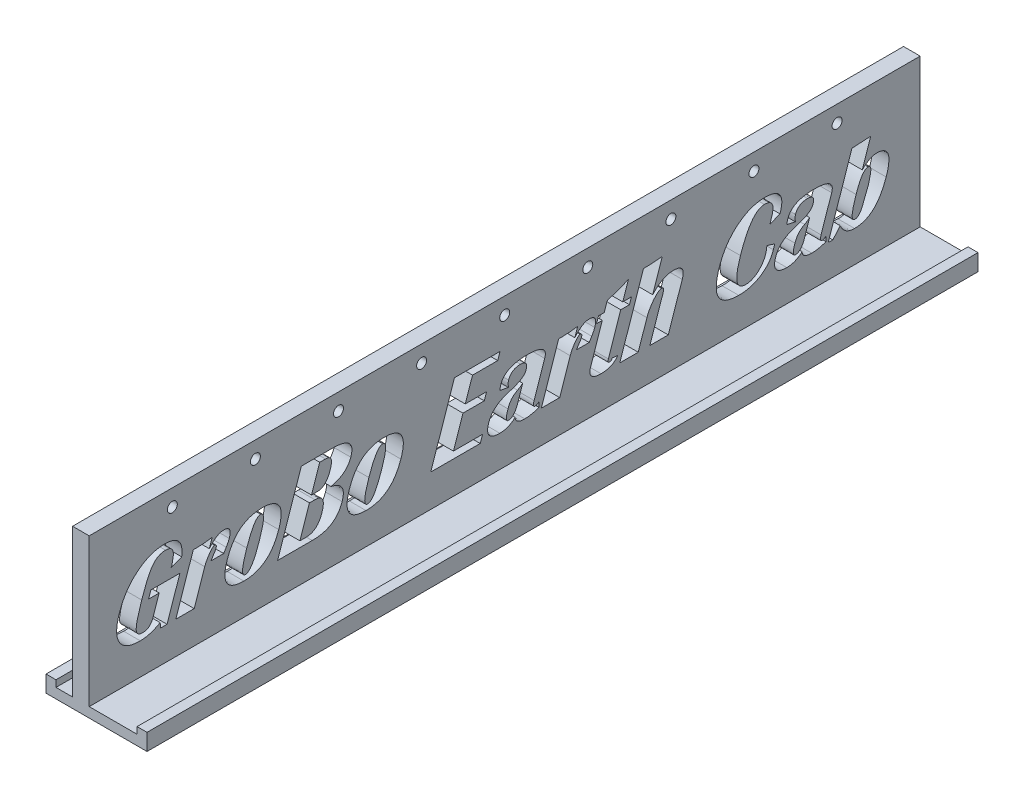
SolidWorks part; units mm, degrees
material "Acrylic (Medium-high impact)"
ref_plane "Front Plane" through (0, 0, 0) normal (0, 0, 1) x (1, 0, 0)
ref_plane "Top Plane" through (0, 0, 0) normal (0, 1, 0) x (1, 0, 0)
ref_plane "Right Plane" through (0, 0, 0) normal (1, 0, 0) x (0, 0, -1)
sketch "Sketch1" plane through (0, 0, 0) normal (0, 0, 1) x (1, 0, 0)
  line L0 (0, 10) -> (0, 0)
  line L1 (0, 0) -> (60.8, 0)
  line L2 (60.8, 0) -> (60.8, 10)
  line L3 (60.8, 10) -> (54.8, 10)
  line L4 (54.8, 10) -> (54.8, 6)
  line L5 (54.8, 6) -> (26, 6)
  line L6 (26, 6) -> (26, 95)
  line L7 (26, 95) -> (16, 95)
  line L8 (16, 95) -> (16, 6)
  line L9 (16, 6) -> (6, 6)
  line L10 (6, 6) -> (6, 10)
  line L11 (6, 10) -> (0, 10)
  dimension "D1" = 10
  dimension "D2" = 10
  dimension "D3" = 6
  dimension "D4" = 6
  dimension "D6" = 10
  dimension "D7" = 60.8
  dimension "D8" = 95
extrude "Boss-Extrude1" add sketch "Sketch1" along normal blind 500
sketch "Sketch2" plane through (26, 0, 0) normal (1, 0, 0) x (0, 0, -1)
  line L0 (-1052.1126, 85) -> (45.5589, 85) construction
  line L1 (-500, 95) -> (-475, 95)
  line L2 (-500, 95) -> (-500, 70)
  line L3 (-500, 70) -> (-475, 70)
  line L4 (-475, 95) -> (-475, 70)
  line L5 (0, 95) -> (-25, 95)
  line L6 (0, 95) -> (0, 70)
  line L7 (0, 70) -> (-25, 70)
  line L8 (-25, 95) -> (-25, 70)
  line L9 (-500, 95) -> (0, 95) construction
  dimension "D1" = 25
  dimension "D2" = 25
  dimension "D3" = 25
  dimension "D4" = 25
  dimension "D5" = 10
extrude "Cut-Extrude1" [suppressed] cut sketch "Sketch2" against normal blind 10
sketch "Sketch3" [suppressed] plane through (25, 0, 0) normal (1, 0, 0) x (0, 0, -1)
  line L0 (-995, 70) -> (-995, 95) construction
  line L1 (-995, 95) -> (-25, 95) construction
  circle A0 centre (-898, 85) radius 3
  dimension "D3" = 6
  dimension "D1" = 97
  dimension "D2" = 10
extrude "Cut-Extrude2" [suppressed] cut sketch "Sketch3" against normal blind 10
pattern_linear "LPattern1" [suppressed] count 9 spacing 97
ref_plane "Plane1" through (0, 0, 250) normal (0, 0, -1) x (-1, 0, 0)
sketch "Sketch4" plane through (26, 0, 0) normal (1, 0, 0) x (0, 0, -1)
  line L0 (-500, 95) -> (0, 95) construction
  line L2 (-500, 6) -> (-500, 95) construction
  circle A0 centre (-450, 85) radius 3
  dimension "D2" = 6
  dimension "D1" = 10
  dimension "D3" = 50
extrude "Cut-Extrude3" cut sketch "Sketch4" against normal blind 10
pattern_linear "LPattern2" count 9 spacing 50 along (0, 0, -1) of "Cut-Extrude3"
sketch "Sketch5" plane through (26, 0, 0) normal (1, 0, 0) x (0, 0, -1)
  text T0 "GroBo Earth Cab" font "Britannic Bold" height 42
extrude "Cut-Extrude4" cut sketch "Sketch5" against normal blind 10
